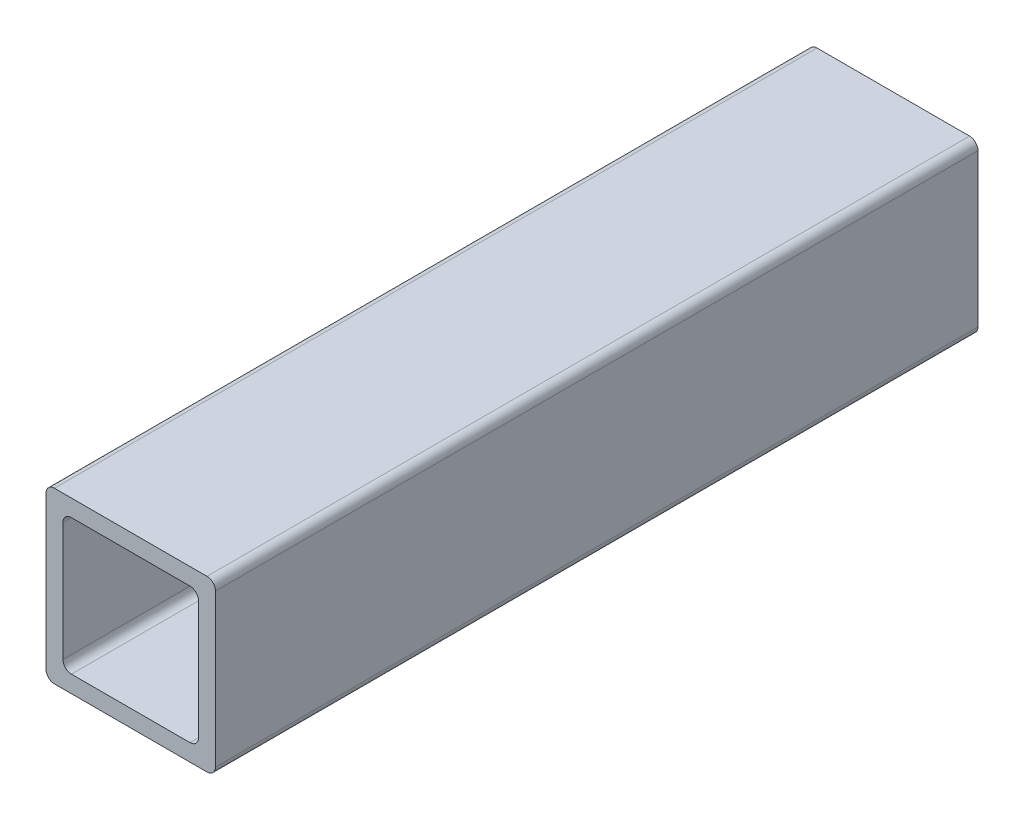
SolidWorks part; units mm, degrees
ref_plane "Plan de face" through (0, 0, 0) normal (0, 0, 1) x (1, 0, 0)
ref_plane "Plan de dessus" through (0, 0, 0) normal (0, 1, 0) x (1, 0, 0)
ref_plane "Plan de droite" through (0, 0, 0) normal (1, 0, 0) x (0, 0, -1)
sketch "Esquisse2" plane through (0, 0, 0) normal (0, 0, 1) x (1, 0, 0)
  line L0 (6, 4) -> (34, 4)
  line L1 (2, 0) -> (38, 0)
  line L2 (0, 2) -> (0, 38)
  line L3 (2, 40) -> (38, 40)
  line L4 (40, 2) -> (40, 38)
  line L5 (36, 6) -> (36, 34)
  line L6 (6, 36) -> (34, 36)
  line L7 (4, 6) -> (4, 34)
  line L8 (4, 4) -> (36, 4) construction
  line L9 (36, 4) -> (36, 36) construction
  line L10 (4, 36) -> (36, 36) construction
  line L11 (4, 4) -> (4, 36) construction
  line L12 (0, 0) -> (40, 0) construction
  line L13 (0, 0) -> (0, 40) construction
  line L14 (0, 40) -> (40, 40) construction
  line L15 (40, 0) -> (40, 40) construction
  arc A0 (34, 4) -> (36, 6) centre (34, 6) ccw
  arc A1 (36, 34) -> (34, 36) centre (34, 34) ccw
  arc A2 (6, 36) -> (4, 34) centre (6, 34) ccw
  arc A3 (4, 6) -> (6, 4) centre (6, 6) ccw
  arc A4 (2, 0) -> (0, 2) centre (2, 2) cw
  arc A5 (0, 38) -> (2, 40) centre (2, 38) cw
  arc A6 (38, 40) -> (40, 38) centre (38, 38) cw
  arc A7 (40, 2) -> (38, 0) centre (38, 2) cw
  point P24 (0, 0)
  dimension "D4" = 2
  dimension "D1" = 40
  dimension "D2" = 40
  dimension "D3" = 4
extrude "Boss.-Extru.1" add sketch "Esquisse2" along normal blind 180
